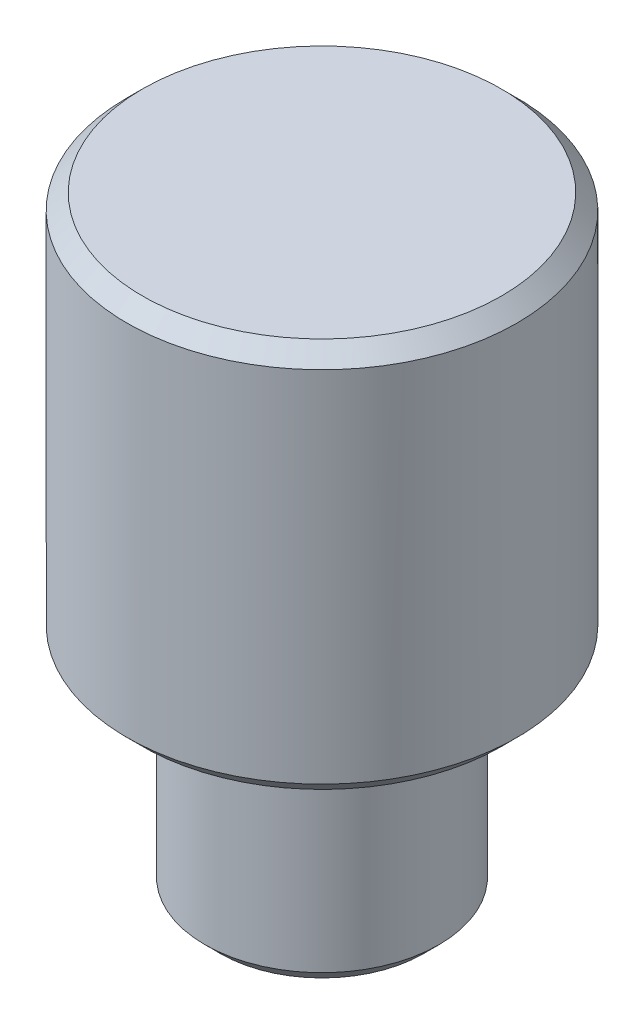
SolidWorks part; units mm, degrees
material "Plain Carbon Steel"
ref_plane "Front Plane" through (0, 0, 0) normal (0, 0, 1) x (1, 0, 0)
ref_plane "Top Plane" through (0, 0, 0) normal (0, 1, 0) x (1, 0, 0)
ref_plane "Right Plane" through (0, 0, 0) normal (1, 0, 0) x (0, 0, -1)
sketch "Sketch1" plane through (0, 0, 0) normal (0, 0, 1) x (1, 0, 0)
  line L0 (0, 0) -> (25, 0)
  line L1 (25, 0) -> (25, -50)
  line L2 (25, -50) -> (15, -50)
  line L3 (15, -50) -> (15, -78)
  line L4 (15, -78) -> (0, -78)
  line L5 (0, -78) -> (0, 0)
  line L6 (0, 5) -> (0, -83) construction
  dimension "D1" = 5
  dimension "D2" = 5
  dimension "D3" = 30
  dimension "D4" = 50
  dimension "D5" = 50
  dimension "D6" = 28
revolve "Revolve1" add sketch "Sketch1" angle 360 about L6
chamfer "Chamfer1" distance 2 angle 45 3 edges at (-15, -78, 0) (-25, -50, 0) (-25, 0, 0)
cosmetic thread "Cosmetic Thread1"
